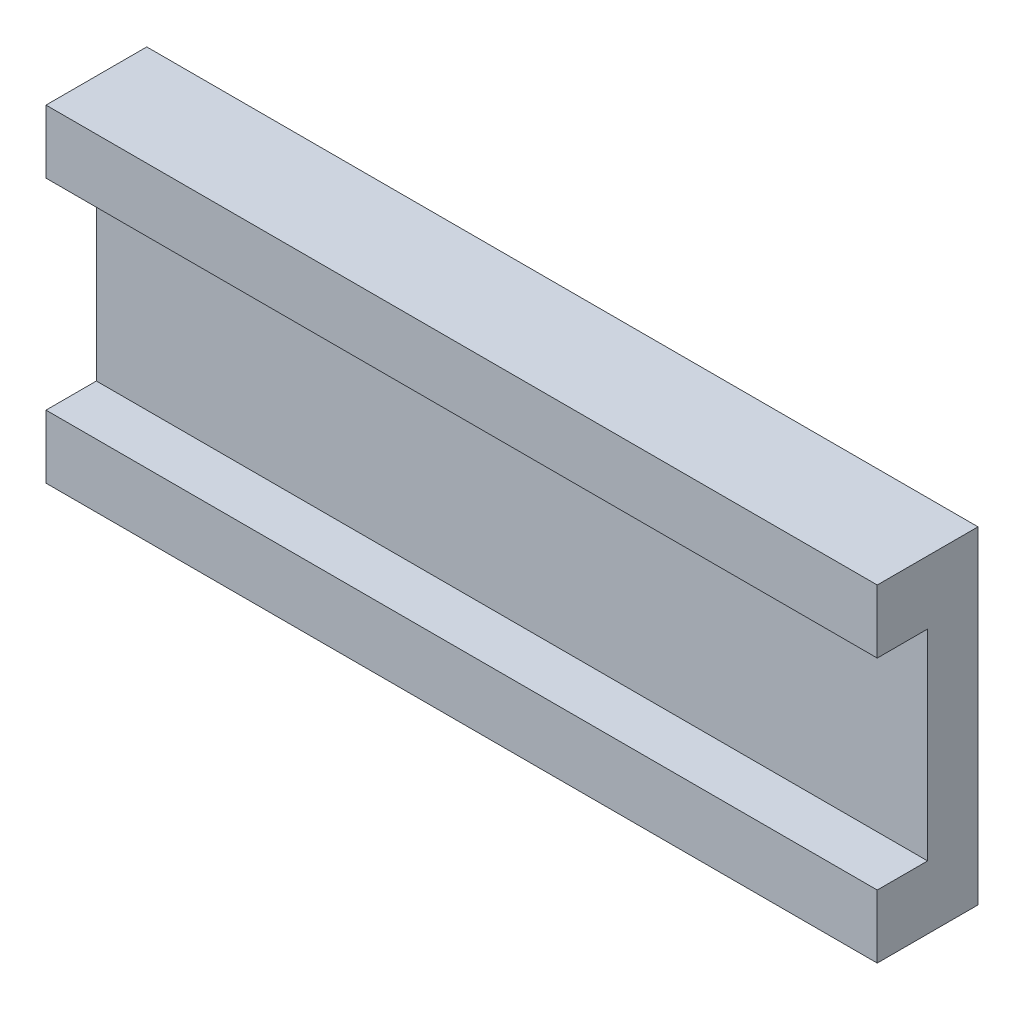
SolidWorks part; units mm, degrees
ref_plane "Front Plane" through (0, 0, 0) normal (0, 0, 1) x (1, 0, 0)
ref_plane "Top Plane" through (0, 0, 0) normal (0, 1, 0) x (1, 0, 0)
ref_plane "Right Plane" through (0, 0, 0) normal (1, 0, 0) x (0, 0, -1)
sketch "Sketch1" plane through (0, 0, 0) normal (0, 0, 1) x (1, 0, 0)
  line L1 (41.91, -16.51) -> (-41.91, -16.51)
  line L2 (41.91, -16.51) -> (41.91, 16.51)
  line L3 (41.91, 16.51) -> (-41.91, 16.51)
  line L4 (-41.91, -16.51) -> (-41.91, 16.51)
  line L5 (41.91, -16.51) -> (-41.91, 16.51) construction
  line L6 (41.91, 16.51) -> (-41.91, -16.51) construction
  point P0 (0, 0)
  dimension "D1" = 83.82
  dimension "D2" = 16.51
extrude "Boss-Extrude1" add sketch "Sketch1" along normal blind 5.08
sketch "Sketch3" plane through (0, 0, 5.08) normal (0, 0, 1) x (1, 0, 0)
  line L0 (41.91, -16.51) -> (41.91, 16.51) construction
  line L1 (-41.91, 16.51) -> (41.91, 16.51)
  line L2 (-41.91, 16.51) -> (-41.91, 10.1278)
  line L3 (-41.91, 10.1278) -> (41.91, 10.1278)
  line L4 (41.91, 16.51) -> (41.91, 10.1278)
  line L5 (-41.91, 16.51) -> (-41.91, -16.51) construction
  line L6 (41.91, -16.51) -> (-41.91, -16.51)
  line L7 (41.91, -16.51) -> (41.91, -10.1278)
  line L8 (41.91, -10.1278) -> (-41.91, -10.1278)
  line L9 (-41.91, -16.51) -> (-41.91, -10.1278)
  dimension "D1" = 6.3822
extrude "Boss-Extrude2" add sketch "Sketch3" along normal blind 5.08
